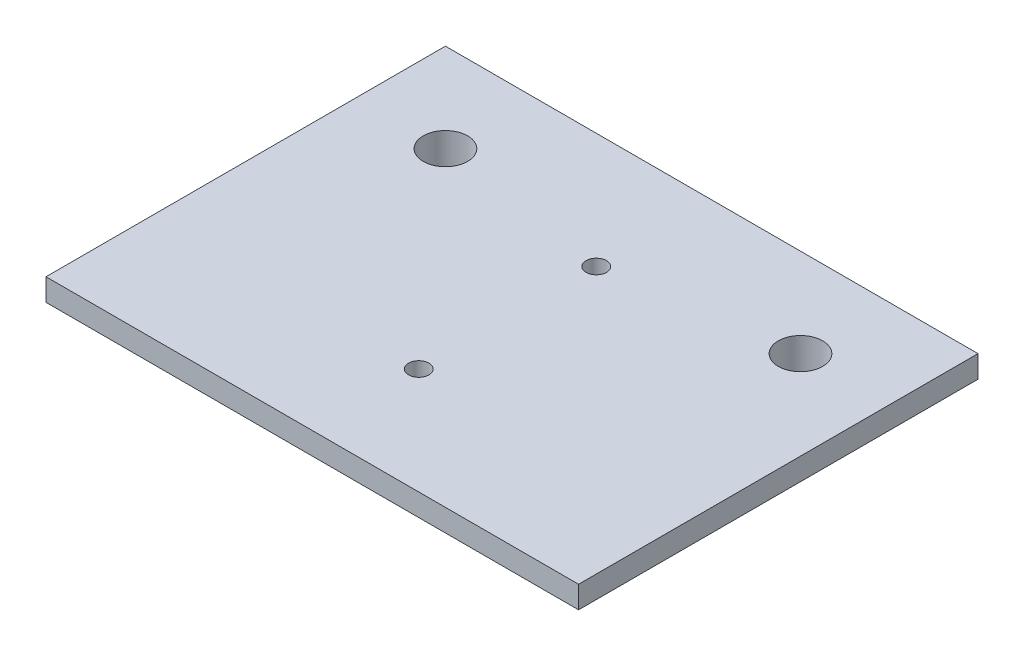
SolidWorks part; units mm, degrees
other "Markup1"
sketch "Sketch1" plane through (0, 0, 0) normal (0.4, 0.515, 0.7581) x (0.8844, 0, -0.4667)
ref_plane "Front Plane" through (0, 0, 0) normal (0, 0, 1) x (1, 0, 0)
ref_plane "Top Plane" through (0, 0, 0) normal (0, 1, 0) x (1, 0, 0)
ref_plane "Right Plane" through (0, 0, 0) normal (1, 0, 0) x (0, 0, -1)
sketch "Sketch2" plane through (-10.6582, 0, 0) normal (0, 1, 0) x (1, 0, 0)
  line L1 (-76.4345, 12.7) -> (-0.2345, 12.7)
  line L2 (-76.4345, 12.7) -> (-76.4345, -44.45)
  line L3 (-76.4345, -44.45) -> (-0.2345, -44.45)
  line L4 (-0.2345, 12.7) -> (-0.2345, -44.45)
  line L5 (-76.4345, 12.7) -> (-0.2345, -44.45) construction
  line L6 (-76.4345, -44.45) -> (-0.2345, 12.7) construction
  circle A1 centre (-63.7345, 0) radius 3.175
  circle A2 centre (-12.9345, 0) radius 3.175
  circle A3 centre (-38.3345, -29.21) radius 1.4605
  circle A4 centre (-38.3345, -3.81) radius 1.4605
  point P1 (0, 0)
  dimension "D1" = 12.7
  dimension "D4" = 50.8
  dimension "D5" = 12.7
  dimension "D6" = 6.35
  dimension "D7" = 6.35
  dimension "D8" = 2.921
  dimension "D9" = 15.24
  dimension "D10" = 2.921
  dimension "D11" = 25.4
  dimension "D12" = 16.51
  dimension "D13" = 38.1
  dimension "D2" = 76.2
  dimension "D3" = 57.15
extrude "Boss-Extrude2" add sketch "Sketch2" along normal blind 3.175
sketch "Sketch7" plane through (0, 0, 0) normal (0, -1, 0) x (1, 0, 0)
  line L1 (-80.7427, 6.35) -> (-68.0427, 6.35)
  line L2 (-80.7427, 6.35) -> (-80.7427, -6.35)
  line L3 (-80.7427, -6.35) -> (-68.0427, -6.35)
  line L4 (-68.0427, 6.35) -> (-68.0427, -6.35)
  line L5 (-80.7427, 6.35) -> (-68.0427, -6.35) construction
  line L6 (-80.7427, -6.35) -> (-68.0427, 6.35) construction
  line L7 (-29.9427, 6.35) -> (-17.2427, 6.35)
  line L8 (-29.9427, 6.35) -> (-29.9427, -6.35)
  line L9 (-29.9427, -6.35) -> (-17.2427, -6.35)
  line L10 (-17.2427, 6.35) -> (-17.2427, -6.35)
  line L11 (-29.9427, 6.35) -> (-17.2427, -6.35) construction
  line L12 (-29.9427, -6.35) -> (-17.2427, 6.35) construction
  line L13 (-55.3427, 35.56) -> (-42.6427, 35.56)
  line L14 (-55.3427, 35.56) -> (-55.3427, 22.86)
  line L15 (-55.3427, 22.86) -> (-42.6427, 22.86)
  line L16 (-42.6427, 35.56) -> (-42.6427, 22.86)
  line L17 (-55.3427, 35.56) -> (-42.6427, 22.86) construction
  line L18 (-55.3427, 22.86) -> (-42.6427, 35.56) construction
  circle A0 centre (-74.3927, 0) radius 3.175
  circle A1 centre (-48.9927, 29.21) radius 1.4605
  circle A2 centre (-23.5927, 0) radius 3.175
  point P0 (-74.3927, 0)
  point P6 (-48.9927, 29.21)
  point P7 (-23.5927, 0)
  dimension "D1" = 12.7
  dimension "D2" = 12.7
  dimension "D3" = 12.7
  dimension "D4" = 12.7
  dimension "D5" = 12.7
  dimension "D6" = 12.7
extrude "Boss-Extrude6" add sketch "Sketch7" along normal blind 3.175
